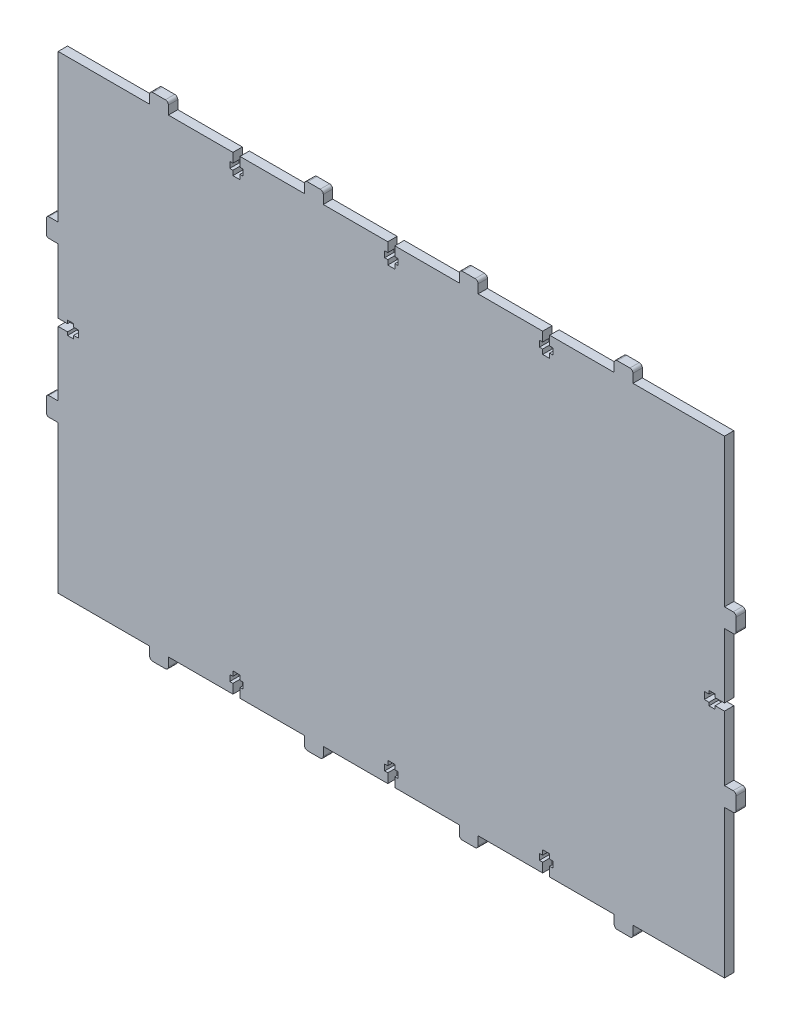
SolidWorks part; units mm, degrees
ref_plane "前视基准面" through (0, 0, 0) normal (0, 0, 1) x (1, 0, 0)
ref_plane "上视基准面" through (0, 0, 0) normal (0, 1, 0) x (1, 0, 0)
ref_plane "右视基准面" through (0, 0, 0) normal (1, 0, 0) x (0, 0, -1)
sketch "草图1" plane through (0, 0, 0) normal (0, 0, 1) x (1, 0, 0)
  line L0 (0, 0) -> (0, -4)
  line L1 (0, -4) -> (-1.35, -4)
  line L2 (-1.35, -4) -> (-1.35, -6.6)
  line L3 (-1.35, -6.6) -> (0, -6.6)
  line L4 (0, -6.6) -> (0, -8.6)
  line L5 (0, -8.6) -> (3, -8.6)
  line L6 (3, -8.6) -> (3, -6.6)
  line L7 (3, -6.6) -> (4.35, -6.6)
  line L8 (4.35, -6.6) -> (4.35, -4)
  line L9 (4.35, -4) -> (3, -4)
  line L10 (3, -4) -> (3, 0)
  line L11 (0, 0) -> (-27.5, 0)
  line L12 (-27.5, 0) -> (-27.5, 5)
  line L13 (-27.5, 5) -> (-35.5, 5)
  line L14 (-35.5, 5) -> (-35.5, 0)
  line L15 (1.5, -8.6) -> (1.5, -6.6) construction
  line L16 (-31.5, 5) -> (-31.5, -50) construction
  line L17 (-67.35, -4) -> (-66, -4)
  line L18 (-66, -6.6) -> (-67.35, -6.6)
  line L19 (-61.65, -6.6) -> (-63, -6.6)
  line L20 (-63, -4) -> (-61.65, -4)
  line L21 (-66, -4) -> (-66, 0)
  line L22 (-66, -8.6) -> (-66, -6.6)
  line L23 (-63, -8.6) -> (-66, -8.6)
  line L24 (-63, -6.6) -> (-63, -8.6)
  line L25 (-67.35, -6.6) -> (-67.35, -4)
  line L26 (-61.65, -4) -> (-61.65, -6.6)
  line L27 (-63, 0) -> (-63, -4)
  line L28 (-63, 0) -> (-35.5, 0)
  line L29 (30.5, 5) -> (38.5, 5)
  line L30 (30.5, 0) -> (30.5, 5)
  line L31 (38.5, 5) -> (38.5, 0)
  line L32 (3, 0) -> (30.5, 0)
  line L33 (66, 0) -> (38.5, 0)
  line L34 (66, 0) -> (66, -4)
  line L35 (64.65, -4) -> (64.65, -6.6)
  line L36 (70.35, -6.6) -> (70.35, -4)
  line L37 (66, -6.6) -> (66, -8.6)
  line L38 (66, -8.6) -> (69, -8.6)
  line L39 (69, -8.6) -> (69, -6.6)
  line L40 (69, -4) -> (69, 0)
  line L41 (66, -4) -> (64.65, -4)
  line L42 (64.65, -6.6) -> (66, -6.6)
  line L43 (69, -6.6) -> (70.35, -6.6)
  line L44 (70.35, -4) -> (69, -4)
  line L45 (67.5, -8.6) -> (67.5, -6.6) construction
  line L46 (69, 0) -> (96.5, 0)
  line L47 (132, 0) -> (104.5, 0)
  line L48 (96.5, 5) -> (96.5, 0)
  line L49 (104.5, 0) -> (104.5, 5)
  line L50 (104.5, 5) -> (96.5, 5)
  line L51 (-64.5, -8.6) -> (-64.5, -6.6) construction
  line L52 (-97.5, 5) -> (-97.5, -50) construction
  line L53 (-66, 0) -> (-93.5, 0)
  line L54 (-93.5, 5) -> (-93.5, 0)
  line L55 (-101.5, 5) -> (-93.5, 5)
  line L56 (-101.5, 0) -> (-101.5, 5)
  line L57 (-129, 0) -> (-101.5, 0)
  line L58 (1.5, -8.6) -> (-140.5, -8.6) construction
  line L59 (-129, 0) -> (-140.5, 0)
  line L60 (132, 0) -> (143.5, 0)
  line L63 (143.5, -200) -> (143.5, 0) construction
  line L64 (143.5, -100) -> (115.133, -100) construction
  line L65 (-129, -200) -> (-140.5, -200)
  line L66 (1.5, -191.4) -> (1.5, -193.4) construction
  line L67 (3, -196) -> (3, -200)
  line L68 (4.35, -196) -> (3, -196)
  line L69 (4.35, -193.4) -> (4.35, -196)
  line L70 (3, -193.4) -> (4.35, -193.4)
  line L71 (3, -191.4) -> (3, -193.4)
  line L72 (0, -191.4) -> (3, -191.4)
  line L73 (0, -193.4) -> (0, -191.4)
  line L74 (-1.35, -193.4) -> (0, -193.4)
  line L75 (-1.35, -196) -> (-1.35, -193.4)
  line L76 (0, -196) -> (-1.35, -196)
  line L77 (0, -200) -> (0, -196)
  line L78 (132, -200) -> (143.5, -200)
  line L79 (67.5, -191.4) -> (67.5, -193.4) construction
  line L80 (104.5, -205) -> (96.5, -205)
  line L81 (104.5, -200) -> (104.5, -205)
  line L82 (96.5, -205) -> (96.5, -200)
  line L83 (132, -200) -> (104.5, -200)
  line L84 (69, -200) -> (96.5, -200)
  line L85 (70.35, -196) -> (69, -196)
  line L86 (69, -193.4) -> (70.35, -193.4)
  line L87 (64.65, -193.4) -> (66, -193.4)
  line L88 (66, -196) -> (64.65, -196)
  line L89 (69, -196) -> (69, -200)
  line L90 (69, -191.4) -> (69, -193.4)
  line L91 (66, -191.4) -> (69, -191.4)
  line L92 (66, -193.4) -> (66, -191.4)
  line L93 (70.35, -193.4) -> (70.35, -196)
  line L94 (64.65, -196) -> (64.65, -193.4)
  line L95 (66, -200) -> (66, -196)
  line L96 (66, -200) -> (38.5, -200)
  line L97 (3, -200) -> (30.5, -200)
  line L98 (38.5, -205) -> (38.5, -200)
  line L99 (30.5, -200) -> (30.5, -205)
  line L100 (30.5, -205) -> (38.5, -205)
  line L101 (1.5, -191.4) -> (-140.5, -191.4) construction
  line L102 (-97.5, -205) -> (-97.5, -150) construction
  line L103 (-64.5, -191.4) -> (-64.5, -193.4) construction
  line L104 (-31.5, -205) -> (-31.5, -150) construction
  line L105 (-129, -200) -> (-101.5, -200)
  line L106 (-101.5, -200) -> (-101.5, -205)
  line L107 (-101.5, -205) -> (-93.5, -205)
  line L108 (-93.5, -205) -> (-93.5, -200)
  line L109 (-66, -200) -> (-93.5, -200)
  line L110 (-63, -200) -> (-35.5, -200)
  line L111 (-63, -200) -> (-63, -196)
  line L112 (-61.65, -196) -> (-61.65, -193.4)
  line L113 (-67.35, -193.4) -> (-67.35, -196)
  line L114 (-63, -193.4) -> (-63, -191.4)
  line L115 (-63, -191.4) -> (-66, -191.4)
  line L116 (-66, -191.4) -> (-66, -193.4)
  line L117 (-66, -196) -> (-66, -200)
  line L118 (-63, -196) -> (-61.65, -196)
  line L119 (-61.65, -193.4) -> (-63, -193.4)
  line L120 (-66, -193.4) -> (-67.35, -193.4)
  line L121 (-67.35, -196) -> (-66, -196)
  line L122 (-35.5, -205) -> (-35.5, -200)
  line L123 (-27.5, -205) -> (-35.5, -205)
  line L124 (-27.5, -200) -> (-27.5, -205)
  line L125 (0, -200) -> (-27.5, -200)
  line L126 (143.5, -98.5) -> (139.5, -98.5)
  line L127 (139.5, -98.5) -> (139.5, -97.15)
  line L128 (139.5, -97.15) -> (136.9, -97.15)
  line L129 (136.9, -97.15) -> (136.9, -98.5)
  line L130 (136.9, -98.5) -> (134.9, -98.5)
  line L131 (134.9, -98.5) -> (134.9, -101.5)
  line L132 (134.9, -101.5) -> (136.9, -101.5)
  line L133 (136.9, -101.5) -> (136.9, -102.85)
  line L134 (136.9, -102.85) -> (139.5, -102.85)
  line L135 (139.5, -102.85) -> (139.5, -101.5)
  line L136 (139.5, -101.5) -> (143.5, -101.5)
  line L137 (134.9, -100) -> (143.5, -100) construction
  line L138 (148.5, -67) -> (143.5, -67) construction
  line L139 (143.5, -71) -> (148.5, -71)
  line L140 (148.5, -71) -> (148.5, -63)
  line L141 (148.5, -63) -> (143.5, -63)
  line L142 (148.5, -133) -> (143.5, -133) construction
  line L143 (148.5, -137) -> (143.5, -137)
  line L144 (148.5, -129) -> (148.5, -137)
  line L145 (143.5, -129) -> (148.5, -129)
  line L146 (143.5, -98.5) -> (143.5, -71)
  line L147 (143.5, -101.5) -> (143.5, -129)
  line L148 (143.5, -137) -> (143.5, -200)
  line L149 (143.5, -63) -> (143.5, 0)
  line L150 (-145.5, -133) -> (-140.5, -133) construction
  line L151 (-145.5, -67) -> (-140.5, -67) construction
  line L154 (-140.5, -101.5) -> (-140.5, -129)
  line L155 (-140.5, -98.5) -> (-140.5, -71)
  line L156 (-140.5, -129) -> (-145.5, -129)
  line L157 (-145.5, -129) -> (-145.5, -137)
  line L158 (-145.5, -137) -> (-140.5, -137)
  line L159 (-145.5, -63) -> (-140.5, -63)
  line L160 (-145.5, -71) -> (-145.5, -63)
  line L161 (-140.5, -71) -> (-145.5, -71)
  line L162 (-136.5, -101.5) -> (-140.5, -101.5)
  line L163 (-136.5, -102.85) -> (-136.5, -101.5)
  line L164 (-133.9, -102.85) -> (-136.5, -102.85)
  line L165 (-133.9, -101.5) -> (-133.9, -102.85)
  line L166 (-131.9, -101.5) -> (-133.9, -101.5)
  line L167 (-131.9, -98.5) -> (-131.9, -101.5)
  line L168 (-133.9, -98.5) -> (-131.9, -98.5)
  line L169 (-133.9, -97.15) -> (-133.9, -98.5)
  line L170 (-136.5, -97.15) -> (-133.9, -97.15)
  line L171 (-136.5, -98.5) -> (-136.5, -97.15)
  line L172 (-140.5, -98.5) -> (-136.5, -98.5)
  line L173 (-140.5, 0) -> (-140.5, -63)
  line L174 (-140.5, -200) -> (-140.5, -137)
  dimension "D1" = 3
  dimension "D2" = 2
  dimension "D3" = 4
  dimension "D4" = 2.6
  dimension "D5" = 1.35
  dimension "D6" = 200
  dimension "D7" = 5
  dimension "D8" = 284
  dimension "D9" = 3
  dimension "D10" = 2
  dimension "D11" = 2.6
  dimension "D12" = 1.35
  dimension "D13" = 8
  dimension "D14" = 5
  dimension "D15" = 29
extrude "凸台-拉伸1" add sketch "草图1" along normal blind 4 contours L33 L31 L29 L30 L32 L10 L9 L8 L7 L6 L5 L4 L3 L2 L1 L0 L11 L12 L13 L14 L28 L27 L20 L26 L19 L24 L23 L22 L18 L25 L17 L21 L53 L54 L55 L56 L57 L59 L173 L159 L160 L161 L155 L172 L171 L170 L169 L168 L167 L166 L165 L164 L163 L162 L154 L156 L157 L158 L174 L65 L105 L106 L107 L108 L109 L117 L121 L113 L120 L116 L115 L114 L119 L112 L118 L111 L110 L122 L123 L124 L125 L77 L76 L75 L74 L73 L72 L71 L70 L69 L68 L67 L97 L99 L100 L98 L96 L95 L88 L94 L87 L92 L91 L90 L86 L93 L85 L89 L84 L82 L80 L81 L83 L78 L148 L143 L144 L145 L147 L136 L135 L134 L133 L132 L131 L130 L129 L128 L127 L126 L146 L139 L140 L141 L149 L60 L47 L49 L50 L48 L46 L40 L44 L36 L43 L39 L38 L37 L42 L35 L41 L34
sketch "草图2" plane through (0, -200, 0) normal (0, -1, 0) x (1, 0, 0)
  line L0 (0, 2) -> (3, 2)
  line L1 (0, 4) -> (0, 0) construction
  line L2 (3, 4) -> (3, 0) construction
  circle A0 centre (1.5, 2) radius 1.5
sketch "草图3" plane through (0, 0, 0) normal (0, 1, 0) x (1, 0, 0)
  line L0 (0, -2) -> (3, -2)
  line L1 (0, -4) -> (0, 0) construction
  line L2 (3, -4) -> (3, 0) construction
  circle A0 centre (1.5, -2) radius 1.5
fillet "圆角1" radius 1 4 edges at (-145.5, -137, 2) (-145.5, -129, 2) (-145.5, -63, 2) (-145.5, -71, 2)
fillet "圆角2" radius 1.3 20 edges at (96.5, 5, 2) (104.5, 5, 2) (38.5, 5, 2) (30.5, 5, 2) (-27.5, 5, 2) (-35.5, 5, 2) (-101.5, 5, 2) (-93.5, 5, 2) (-101.5, -205, 2) (-93.5, -205, 2) (-35.5, -205, 2) (-27.5, -205, 2) (30.5, -205, 2) (38.5, -205, 2) (96.5, -205, 2) (104.5, -205, 2) (148.5, -137, 2) (148.5, -129, 2) (148.5, -63, 2) (148.5, -71, 2)
